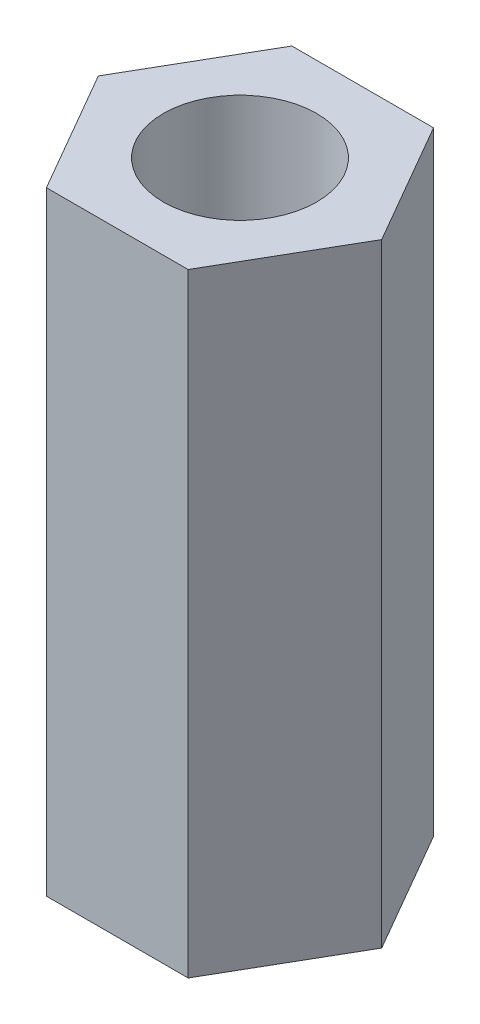
SolidWorks part; units mm, degrees
material "黄铜"
ref_plane "前视基准面" through (0, 0, 0) normal (0, 0, 1) x (1, 0, 0)
ref_plane "上视基准面" through (0, 0, 0) normal (0, 1, 0) x (1, 0, 0)
ref_plane "右视基准面" through (0, 0, 0) normal (1, 0, 0) x (0, 0, -1)
sketch "草图1" plane through (0, 0, 0) normal (0, 1, 0) x (1, 0, 0)
  line L1 (2.3094, 0) -> (1.1547, 2)
  line L2 (1.1547, 2) -> (-1.1547, 2)
  line L3 (-1.1547, 2) -> (-2.3094, 0)
  line L4 (-2.3094, 0) -> (-1.1547, -2)
  line L5 (-1.1547, -2) -> (1.1547, -2)
  line L6 (1.1547, -2) -> (2.3094, 0)
  circle A0 centre (0, 0) radius 2 construction
  point P1 (0, 0)
  dimension "D1" = 4
extrude "凸台-拉伸1" add sketch "草图1" along normal blind 10
hole_wizard "孔1" positions "草图2" profile "草图3" legacy end condition up to next
sketch "草图2" plane through (0, 10, 0) normal (0, 1, 0) x (1, 0, 0)
  point P0 (0, 0)
sketch "草图3" plane through (0, 10, 0) normal (1, 0, 0) x (0, 0, 1)
  line L0 (0, 0) -> (0, 10)
  line L1 (0, 10) -> (1.25, 10)
  line L2 (1.25, 10) -> (1.25, 0)
  line L3 (1.25, 0) -> (0, 0)
  line L4 (0, 110) -> (0, -10) construction
  dimension "直径" = 2.5
  dimension "深度" = 10
